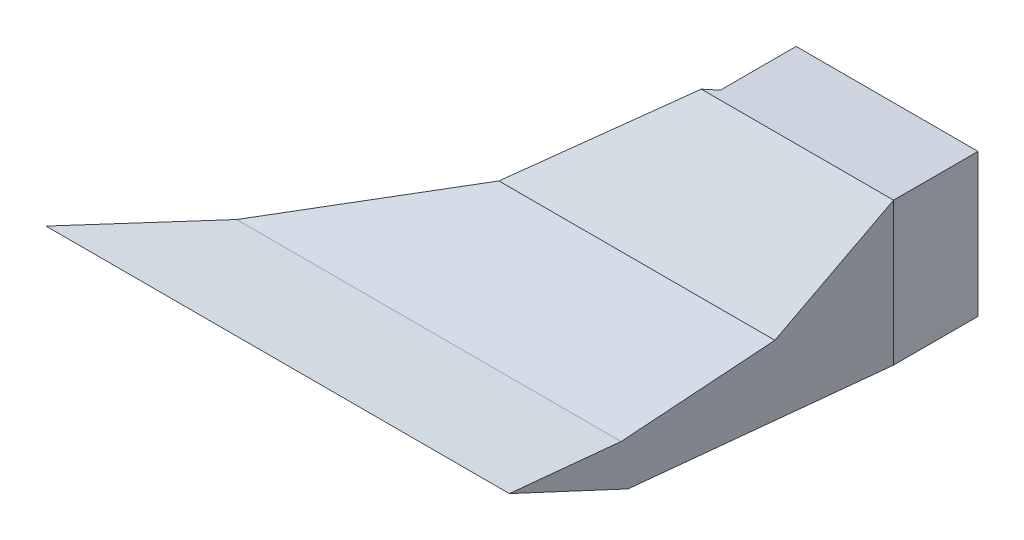
SolidWorks part; units mm, degrees
ref_plane "Front"
ref_plane "Top" through (0, 0, 0) normal (0, 1, 0) x (1, 0, 0)
ref_plane "Right" through (0, 0, 0) normal (1, 0, 0) x (0, 0, -1)
sketch "Side base sketch" plane through (0, 0, 0) normal (-1, 0, 0) x (0, 0, 1)
  line L0 (0, 13.2) -> (8.4913, 5)
  line L1 (0, 0) -> (6, -1)
  line L2 (6, -1) -> (19, -3.1667)
  line L3 (8.4913, 5) -> (19.4913, 0.803)
  line L4 (19.4913, 0.803) -> (27.4913, -0.5303)
  line L5 (27.4913, -0.5303) -> (19, -3.1667)
  line L6 (0, 13.2) -> (0, 0)
  dimension "D1" = 6
  dimension "D2" = 6
  dimension "D3" = 1
  dimension "D4" = 46
  dimension "D5" = 13
  dimension "D6" = 11
  dimension "D7" = 4
  dimension "D8" = 8
  dimension "D9" = 13.2
extrude "Side base" add sketch "Side base sketch" against normal blind 0.8
pattern_linear "Side base 2" count 2 spacing 50 along (1, 0, 0) of bodies 108
sketch "Wall base sketch" plane through (0.8, 0, 0) normal (1, 0, 0) x (0, 0, -1)
  line L0 (0, 12.0879) -> (-8.0533, 4.3109)
  line L1 (-25.7916, -1.058) -> (-19.2809, 0.0271)
  line L2 (-27.4913, -0.5303) -> (-19.4913, 0.803)
  line L3 (-19, -3.4019) -> (-19, 4.6777) construction
  line L4 (0, 13.2) -> (0, 0) construction
  line L5 (0, 0) -> (-19, -3.1667) construction
  line L6 (-19.4913, 0.803) -> (-8.4913, 5)
  line L7 (-19.2809, 0.0271) -> (-8.0533, 4.3109)
  line L8 (-8.4913, 5) -> (0, 13.2) construction
  line L9 (0, 0.811) -> (-19, -2.3556)
  line L11 (-19, -2.3556) -> (-19, -3.1667)
  line L12 (-19, -3.1667) -> (0, 0)
  line L13 (0, 0) -> (0, 0.811)
  line L14 (-25.7916, -1.058) -> (-27.4913, -0.5303)
  line L16 (-8.4913, 5) -> (0, 13.2)
  line L17 (0, 13.2) -> (0, 12.0879)
  line L18 (-19, -3.1667) -> (-27.4913, -0.5303) construction
  point P2 (-19.4913, 0.803)
  point P4 (-19.2809, 0.0271)
  dimension "D1" = 0.8
  dimension "D2" = 0.8
  dimension "D3" = 0.8
  dimension "D4" = 0.8
extrude "Front back walls" add sketch "Wall base sketch" along normal up to next
sketch "Base sketch" plane through (0, 0, 0) normal (0, 0, -1) x (-1, 0, 0)
  line L0 (-50, 12.0879) -> (-0.8, 12.0879) construction
  line L1 (0, 13.2) -> (-50.8, 13.2)
  line L2 (0, 13.2) -> (0, 0)
  line L3 (0, 0) -> (-50.8, 0)
  line L4 (-50.8, 13.2) -> (-50.8, 0)
  line L5 (-50, 0.811) -> (-34.8, 0.811)
  line L6 (-50, 0.811) -> (-50, 12.0879)
  line L7 (-50, 12.0879) -> (-34.8, 12.0879)
  line L8 (-34.8, 0.811) -> (-34.8, 12.0879)
  dimension "D1" = 15.2
extrude "Base" add sketch "Base sketch" along normal blind 0.8
sketch "Attachment base sketch" plane through (0, 0, -0.8) normal (0, 0, -1) x (-1, 0, 0)
  line L0 (-50.8, 0) -> (0, 0) construction
  line L1 (-50.8, 13.2) -> (-34, 13.2)
  line L2 (-50.8, 13.2) -> (-50.8, 0)
  line L3 (-50.8, 0) -> (-34, 0)
  line L4 (-34, 13.2) -> (-34, 0)
  line L5 (-34.8, 0.811) -> (-34.8, 12.0879) construction
  line L7 (-34.8, 12.0879) -> (-50, 12.0879)
  line L8 (-34.8, 12.0879) -> (-34.8, 0.811)
  line L9 (-34.8, 0.811) -> (-50, 0.811)
  line L10 (-50, 12.0879) -> (-50, 0.811)
  dimension "D1" = 0.8
extrude "Attachment base" add sketch "Attachment base sketch" along normal blind 7
sketch "Sketch11" plane through (0, 0, -7.8) normal (0, 0, -1) x (-1, 0, 0)
  line L0 (-34, 13.2) -> (-50.8, 13.2) construction
  line L1 (-50, 12.0879) -> (-34.8, 12.0879)
  line L2 (-50, 12.0879) -> (-50, 12.4)
  line L3 (-50, 12.4) -> (-34.8, 12.4)
  line L4 (-34.8, 12.0879) -> (-34.8, 12.4)
  dimension "D1" = 0.8
extrude "Pipe top extra cutaway" cut sketch "Sketch11" against normal up to surface (7.8 mm away)
sketch "Sketch1" plane through (0, 0, -7.8) normal (0, 0, -1) x (-1, 0, 0)
  line L0 (-50, 12.4) -> (-50, 0.811) construction
  line L1 (-50, 12.4) -> (-34.8, 12.4)
  line L2 (-50, 12.4) -> (-50, 0.811)
  line L3 (-50, 0.811) -> (-34.8, 0.811)
  line L4 (-34.8, 12.4) -> (-34.8, 0.811)
extrude "Fan base" add sketch "Sketch1" along normal blind 0.1 separate body
sketch "Sketch4" plane through (0.8, 0, 0) normal (1, 0, 0) x (0, 0, -1)
  line L0 (-25.7916, -1.058) -> (-19, -3.1667)
  line L1 (-19, -3.1667) -> (-19, -2.3556)
  line L2 (-19, -2.3556) -> (0, 0.811)
  line L3 (0, 0.811) -> (0, 12.0879)
  line L4 (-8.0533, 4.3109) -> (0, 12.0879) construction
  line L5 (0, 12.0879) -> (0, 0.811) construction
  line L6 (0, 12.0879) -> (-8.0533, 4.3109)
  line L7 (-8.0533, 4.3109) -> (-19.2809, 0.0271)
  line L8 (-25.7916, -1.058) -> (-19.2809, 0.0271)
extrude "Left right wall removal" cut sketch "Sketch4" against normal through all both and the other way through all
ref_point "Cutaway left intersection point" parameters "D1"=8
ref_plane "Cutaway left plane" through (46.834, 0, 13.6287) normal (0.9602, 0, 0.2794) x (0.2794, 0, -0.9602)
sketch "Sketch6" plane through (46.834, 0, 13.6287) normal (0.9602, 0, 0.2794) x (0.2794, 0, -0.9602)
  line L1 (-14.4376, -3.1667) -> (14.1941, -3.1667)
  line L2 (-14.4376, -3.1667) -> (-14.4376, 13.2)
  line L3 (-14.4376, 13.2) -> (14.1941, 13.2)
  line L4 (14.1941, -3.1667) -> (14.1941, 13.2)
  point P4 (-14.4376, -0.5303)
  point P6 (-5.5941, -3.1667)
extrude "Cutaway left" cut sketch "Sketch6" along normal through all
sketch "Sketch7" plane through (46.834, 0, 13.6287) normal (0.9602, 0, 0.2794) x (0.2794, 0, -0.9602)
  line L0 (-5.5941, -2.3556) -> (-5.5941, -3.1667)
  line L1 (-5.5941, -3.1667) -> (-12.6674, -1.058)
  line L2 (-12.6674, -1.058) -> (-5.8866, 0.0271)
  line L3 (5.8067, 4.3109) -> (14.1941, 12.0879)
  line L4 (14.1941, 12.0879) -> (14.1941, 0.811)
  line L5 (14.1941, 0.811) -> (-5.5941, -2.3556)
  line L6 (-5.8866, 0.0271) -> (5.8067, 4.3109)
extrude "Left wall" add sketch "Sketch7" along direction (-1, 0, 0) on the side against the normal blind 0.8332
ref_point "Cutaway right intersection point 1" parameters "D1"=4
ref_point "Cutaway right intersection point 2" parameters "D1"=4
ref_plane "Cutaway right plane" through (13.5167, 0, 16.2441) normal (0.6396, 0, 0.7687) x (0.7687, 0, -0.6396)
sketch "Sketch9" plane through (13.5167, 0, 16.2441) normal (0.6396, 0, 0.7687) x (0.7687, 0, -0.6396)
  line L1 (26.6471, 13.2) -> (-17.5841, 13.2)
  line L2 (26.6471, 13.2) -> (26.6471, -3.1667)
  line L3 (26.6471, -3.1667) -> (-17.5841, -3.1667)
  line L4 (-17.5841, 13.2) -> (-17.5841, -3.1667)
extrude "Cutaway right" cut sketch "Sketch9" against normal through all
sketch "Sketch10" plane through (13.5167, 0, 16.2441) normal (-0.6396, 0, -0.7687) x (-0.7687, 0, 0.6396)
  line L0 (-25.3964, 12.0879) -> (-25.3964, 0.811)
  line L1 (-25.3964, 0.811) -> (4.3086, -2.3556)
  line L2 (4.3086, -2.3556) -> (4.3086, -3.1667)
  line L3 (4.3086, -3.1667) -> (14.9267, -1.058)
  line L4 (14.9267, -1.058) -> (4.7478, 0.0271)
  line L5 (-12.8057, 4.3109) -> (-25.3964, 12.0879)
  line L6 (4.7478, 0.0271) -> (-12.8057, 4.3109)
extrude "Right wall" add sketch "Sketch10" along direction (-1, 0, 0) on the side against the normal blind 1.2507
ref_plane "Air flow cut plane" through (0, 0, 27.4913) normal (0, 0, 1) x (1, 0, 0)
equation "\"wall_thicknes\"=0.8"
equation "\"D1@Base\" = \"wall_thicknes\""
equation "\"D1@Wall base sketch\"=\"wall_thicknes\""
equation "\"D1@Side base\"=\"wall_thicknes\""
equation "\"D2@Wall base sketch\"=\"wall_thicknes\""
equation "\"D3@Wall base sketch\"=\"wall_thicknes\""
equation "\"D1@Base sketch\"=\"wall_thicknes\"*-2+16.8"
equation "\"D1@Attachment base sketch\"=\"wall_thicknes\""
equation "\"D1@Left wall\"=\"left_wall_thickness\""
equation "\"D1@Sketch11\"=\"wall_thicknes\""
equation "\"left_wall_thickness\"= 0.83318430202930948562"
equation "\"right_wall_thickness\"= 1.25073472653581935106"
equation "\"D1@Right wall\"=\"right_wall_thickness\""
equation "\"D4@Wall base sketch\"=\"wall_thicknes\""
